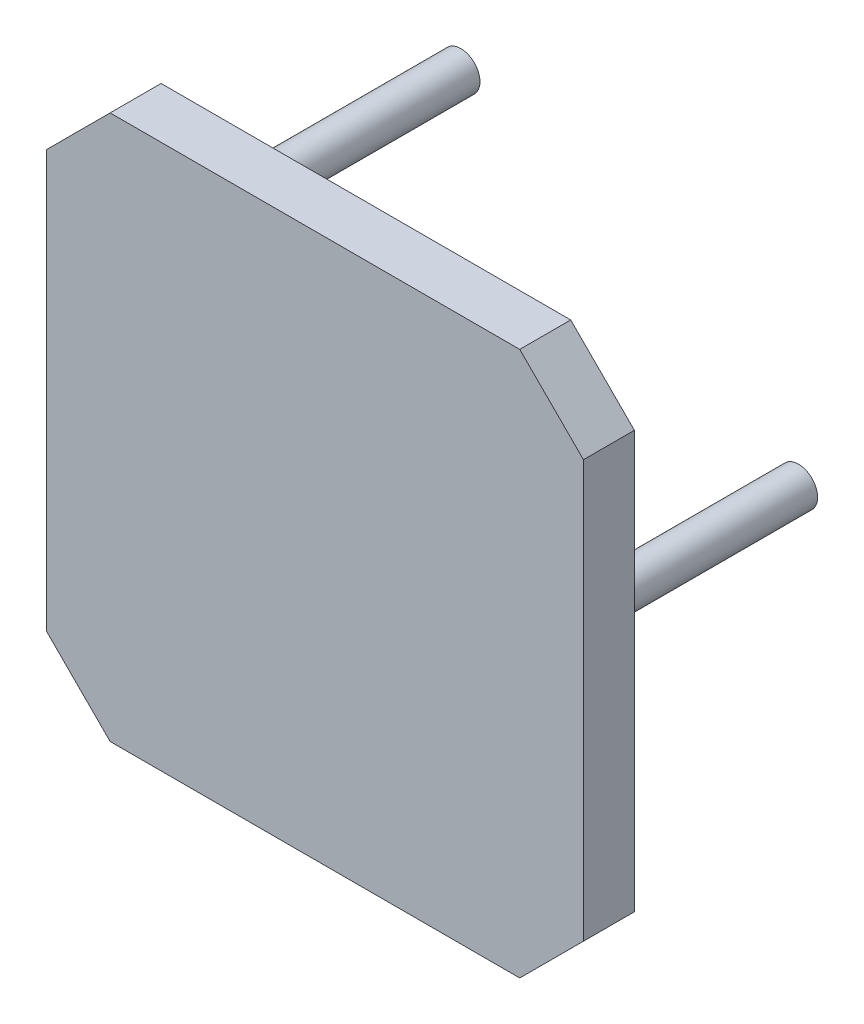
SolidWorks part; units mm, degrees
ref_plane "Plan de face" through (0, 0, 0) normal (0, 0, 1) x (1, 0, 0)
ref_plane "Plan de dessus" through (0, 0, 0) normal (0, 1, 0) x (1, 0, 0)
ref_plane "Plan de droite" through (0, 0, 0) normal (1, 0, 0) x (0, 0, -1)
sketch "Esquisse1" plane through (0, 0, 0) normal (0, 0, 1) x (1, 0, 0)
  line L1 (55, 0) -> (-55, 0) construction
  line L2 (-16.0307, -21.3658) -> (-16.0307, 21.3658)
  line L3 (-16.0307, 21.3658) -> (26.1208, 21.3658)
  line L4 (26.1208, 21.3658) -> (26.1208, -21.3658)
  line L5 (-16.0307, -21.3658) -> (26.1208, -21.3658)
  point P14 (26.1208, 0)
  point P19 (-16.0307, 0)
extrude "Boss.-Extru.1" add sketch "Esquisse1" along normal blind 4
chamfer "Chanfrein1" distance 5 angle 45 4 edges at (-16.0307, -21.3658, 2) (-16.0307, 21.3658, 2) (26.1208, -21.3658, 2) (26.1208, 21.3658, 2)
sketch "Esquisse3" plane through (0, 0, 0) normal (0, 0, -1) x (-1, 0, 0)
  line L0 (2.2, 0) -> (-2.2, 0) construction
  line L1 (0, 2.2) -> (0, -2.2) construction
  circle A0 centre (-20, 0) radius 1.5
  circle A1 centre (6.5, 15) radius 1.5
  circle A2 centre (6.5, -15) radius 1.5
  dimension "D1" = 20
  dimension "D2" = 15
  dimension "D3" = 6.5
extrude "Boss.-Extru.3" add sketch "Esquisse3" along normal blind 19
